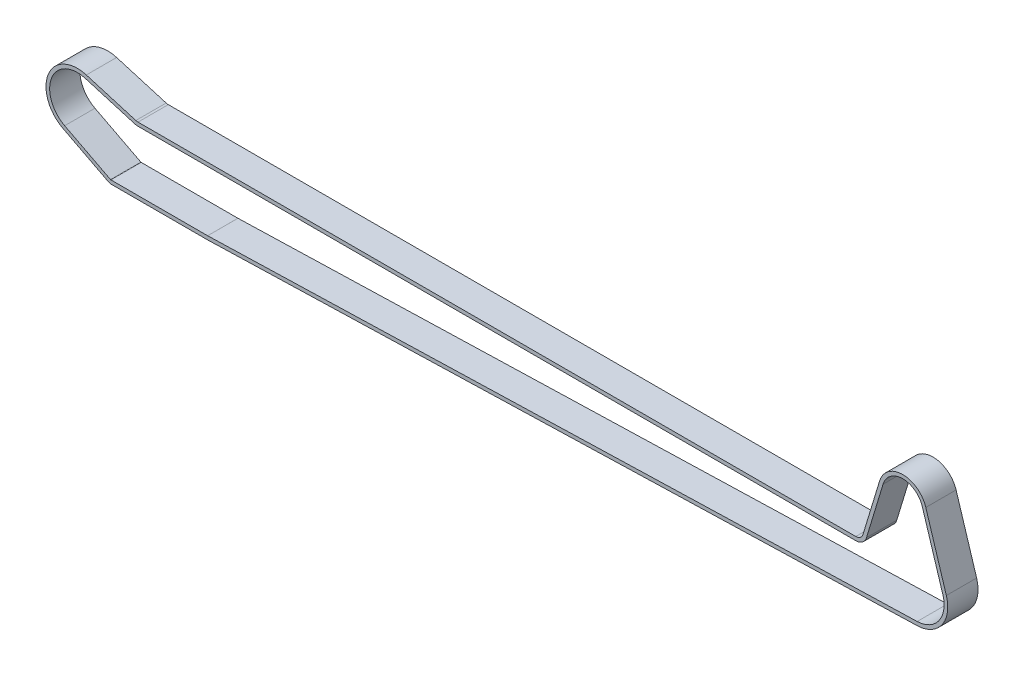
SolidWorks part; units mm, degrees
ref_plane "前视基准面" through (0, 0, 0) normal (0, 0, 1) x (1, 0, 0)
ref_plane "上视基准面" through (0, 0, 0) normal (0, 1, 0) x (1, 0, 0)
ref_plane "右视基准面" through (0, 0, 0) normal (1, 0, 0) x (0, 0, -1)
sketch "草图1" plane through (0, 0, 0) normal (0, 0, 1) x (1, 0, 0)
  line L0 (0, -38.5341) -> (0, 38.5341) construction
  line L1 (-135.8978, 8.793) -> (-119.54, 3.9521)
  line L2 (-118.49, 3.8) -> (118.49, 3.8)
  line L3 (122.0302, 6.4245) -> (127.5128, 24.4708)
  line L4 (140.4737, 24.5149) -> (147.2557, 2.7252)
  line L11 (-127.5, -16) -> (-95.5, -16)
  line L12 (-142.7071, -8.1479) -> (-127.5, -16)
  line L13 (-95.5, -16) -> (138.7674, -9.1661)
  line L14 (141.6195, 24.8715) -> (148.4015, 3.0818)
  line L15 (-95.4825, -17.2) -> (138.8024, -10.3656)
  line L16 (-127.7915, -17.2) -> (-95.4825, -17.2)
  line L17 (-143.2577, -9.2142) -> (-127.7915, -17.2)
  line L18 (-135.5573, 9.9437) -> (-119.1994, 5.1028)
  line L19 (-118.49, 5) -> (118.49, 5)
  line L20 (120.882, 6.7733) -> (126.3646, 24.8197)
  arc A5 (-135.8978, 8.793) -> (-142.7071, -8.1479) centre (-138.5, 0) ccw
  arc A6 (-119.54, 3.9521) -> (-118.49, 3.8) centre (-118.49, 7.5) ccw
  arc A7 (122.0302, 6.4245) -> (118.49, 3.8) centre (118.49, 7.5) cw
  arc A8 (147.2557, 2.7252) -> (138.7674, -9.1661) centre (138.5, 0) cw
  arc A9 (140.4737, 24.5149) -> (127.5128, 24.4708) centre (134, 22.5) ccw
  arc A15 (148.4015, 3.0818) -> (138.8024, -10.3656) centre (138.5, 0) cw
  arc A16 (-135.5573, 9.9437) -> (-143.2577, -9.2142) centre (-138.5, 0) ccw
  arc A17 (-119.1994, 5.1028) -> (-118.49, 5) centre (-118.49, 7.5) ccw
  arc A18 (120.882, 6.7733) -> (118.49, 5) centre (118.49, 7.5) cw
  arc A19 (141.6195, 24.8715) -> (126.3646, 24.8197) centre (134, 22.5) ccw
  point P3 (0, 0)
  dimension "D1" = 277
  dimension "D2" = 18.34
  dimension "D3" = 7.4
  dimension "D4" = 7.5
  dimension "D5" = 20.01
  dimension "D6" = 4.5
  dimension "D7" = 22.5
  dimension "D8" = 13.56
  dimension "D9" = 11
  dimension "D10" = 16
  dimension "D11" = 32
  dimension "D12" = 1.2
extrude "凸台-拉伸1" add sketch "草图1" along normal mid plane 10
fillet "圆角1" radius 0.3 2 edges at (-95.5, -16, 0) (-127.5, -16, 0)
fillet "圆角2" radius 1.5 2 edges at (-95.4825, -17.2, 0) (-127.7915, -17.2, 0)
